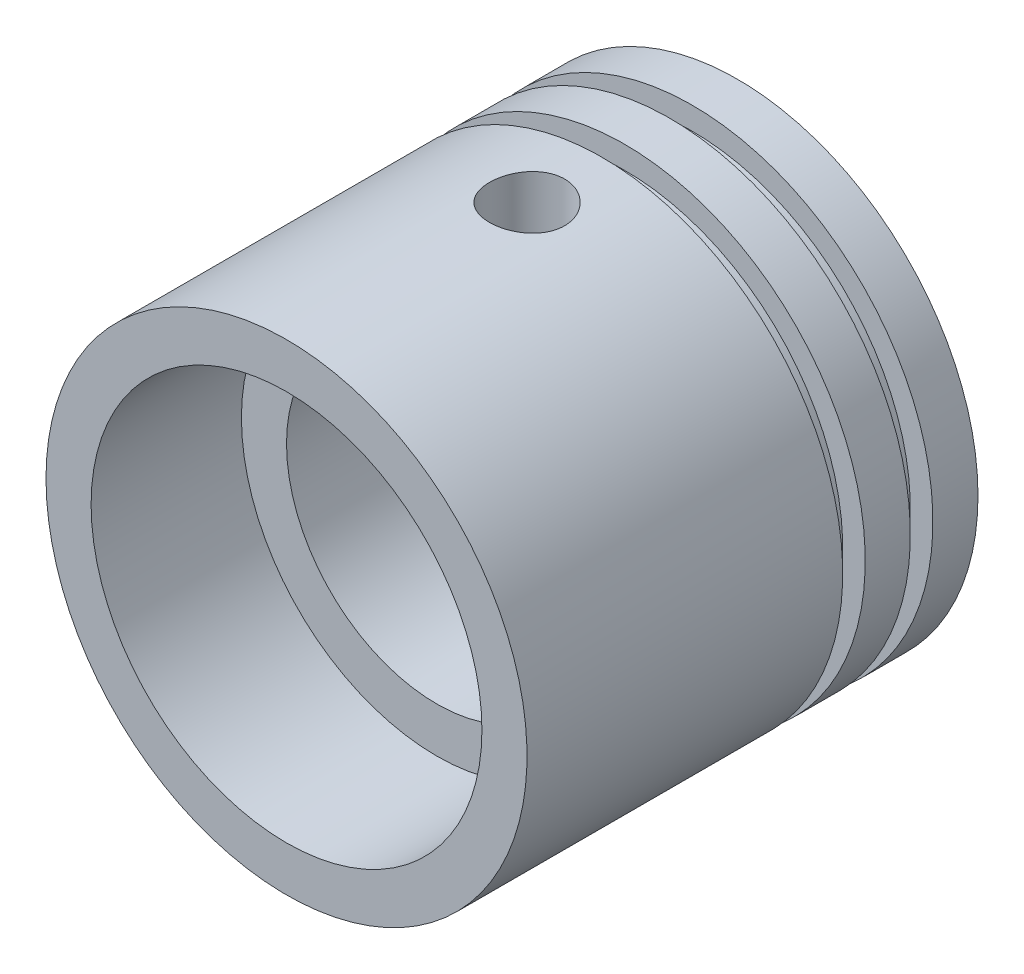
SolidWorks part; units mm, degrees
ref_plane "Front Plane" through (0, 0, 0) normal (0, 0, 1) x (1, 0, 0)
ref_plane "Top Plane" through (0, 0, 0) normal (0, 1, 0) x (1, 0, 0)
ref_plane "Right Plane" through (0, 0, 0) normal (1, 0, 0) x (0, 0, -1)
sketch "Sketch1" plane through (0, 0, 0) normal (0, 1, 0) x (1, 0, 0)
  line L0 (0, 0) -> (0, -95.7307) construction
  line L1 (3.473, -0.3038) -> (16, -2.5127)
  line L2 (16, -2.5127) -> (16, -5.5127)
  line L3 (16, -5.5127) -> (14.5, -5.5127)
  line L4 (14.5, -5.5127) -> (14.5, -7.0127)
  line L5 (14.5, -7.0127) -> (16, -7.0127)
  line L6 (16, -7.0127) -> (16, -10.0127)
  line L7 (16, -10.0127) -> (14.5, -10.0127)
  line L8 (14.5, -10.0127) -> (14.5, -11.5127)
  line L9 (14.5, -11.5127) -> (16, -11.5127)
  line L10 (16, -11.5127) -> (16, -32.5127)
  line L11 (16, -32.5127) -> (-16, -32.5127)
  line L12 (-16, -11.5127) -> (-16, -32.5127)
  line L13 (-14.5, -11.5127) -> (-16, -11.5127)
  line L14 (-14.5, -10.0127) -> (-14.5, -11.5127)
  line L15 (-16, -10.0127) -> (-14.5, -10.0127)
  line L16 (-16, -7.0127) -> (-16, -10.0127)
  line L17 (-14.5, -7.0127) -> (-16, -7.0127)
  line L18 (-14.5, -5.5127) -> (-14.5, -7.0127)
  line L19 (-16, -5.5127) -> (-14.5, -5.5127)
  line L20 (-16, -2.5127) -> (-16, -5.5127)
  line L21 (-3.473, -0.3038) -> (-16, -2.5127)
  line L22 (0, 0) -> (17.1905, 0) construction
  line L23 (-10, -8.5127) -> (10, -8.5127)
  line L24 (10, -8.5127) -> (10, -22.5127)
  line L25 (10, -22.5127) -> (13, -22.5127)
  line L26 (13, -22.5127) -> (13, -32.5127)
  line L27 (-13, -22.5127) -> (-13, -32.5127)
  line L28 (-10, -22.5127) -> (-13, -22.5127)
  line L29 (-10, -8.5127) -> (-10, -22.5127)
  line L30 (-10, -22.5127) -> (10, -22.5127)
  line L31 (0, -32.5127) -> (0, 0)
  arc A0 (-3.473, -0.3038) -> (3.473, -0.3038) centre (0, -20) cw
  point P33 (0, -32.5127)
  point P38 (0, -8.5127)
  point P39 (0, 0)
  dimension "D1" = 20
  dimension "D2" = 10
  dimension "D3" = 21
  dimension "D4" = 1.5
  dimension "D5" = 3
  dimension "D6" = 29
  dimension "D7" = 32
  dimension "D8" = 20
  dimension "D9" = 26
  dimension "D10" = 10
  dimension "D11" = 24
revolve "Revolve1" add sketch "Sketch1" angle 360 about L0
sketch "Sketch3" plane through (0, 0, 0) normal (0, 1, 0) x (0, 0, -1)
  line L0 (-32.5127, 16) -> (-32.5127, -16) construction
  circle A0 centre (-16.5127, 0) radius 2.5
  dimension "D1" = 5
  dimension "D2" = 16
extrude "Cut-Extrude1" cut sketch "Sketch3" against normal mid plane 80
